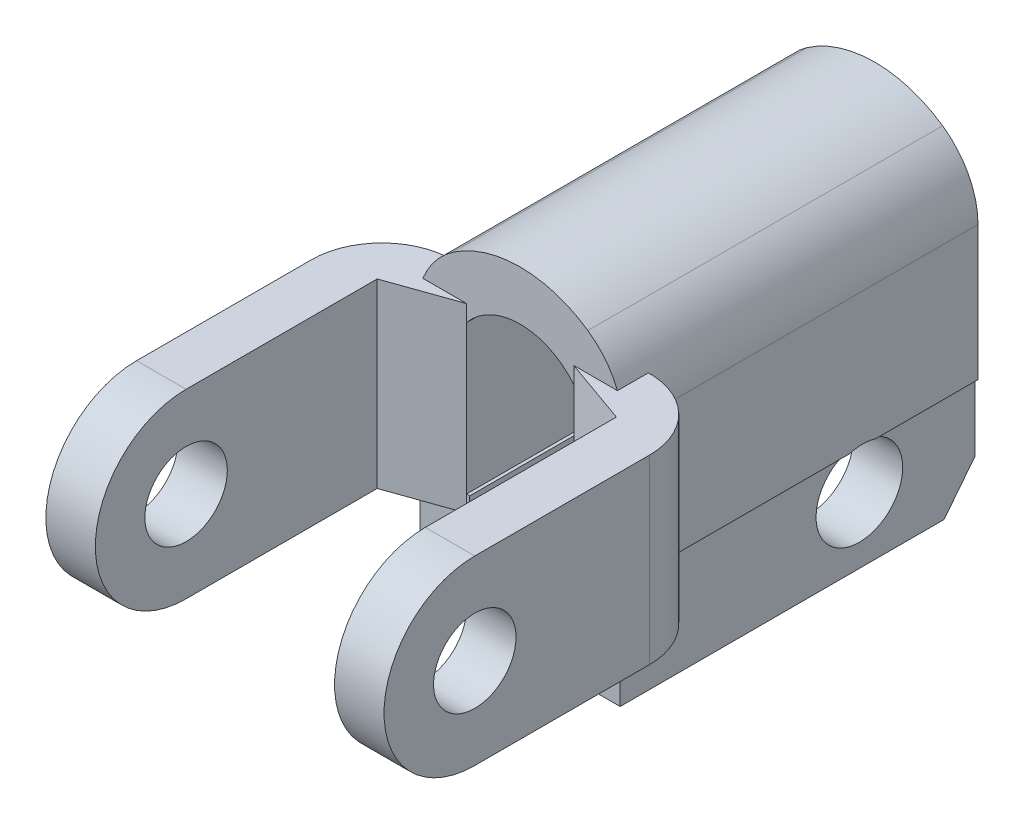
SolidWorks part; units mm, degrees
ref_plane "Front Plane" through (0, 0, 0) normal (0, 0, 1) x (1, 0, 0)
ref_plane "Top Plane" through (0, 0, 0) normal (0, 1, 0) x (1, 0, 0)
ref_plane "Right Plane" through (0, 0, 0) normal (1, 0, 0) x (0, 0, -1)
sketch "Sketch1" plane through (0, 0, 0) normal (0, 0, 1) x (1, 0, 0)
  line L0 (0, -9) -> (0, 9) construction
  line L1 (-6.5, 9) -> (-6.5, -9)
  line L2 (6.5, 9) -> (6.5, -9)
  line L3 (-6.5, -9) -> (-6.1191, -9)
  line L4 (-6.1191, -9) -> (-6.1191, -22)
  line L5 (6.1191, -9) -> (6.1191, -22)
  line L6 (6.5, -9) -> (6.1191, -9)
  line L7 (12.1191, -8.9892) -> (12.1191, -22)
  line L8 (12.5, -8.9892) -> (12.1191, -8.9892)
  line L9 (12.5, 7.3083) -> (12.5, -8.9892)
  line L10 (-12.5, 7.3083) -> (-12.5, -8.9607)
  line L11 (-12.5, -8.9607) -> (-12.1191, -8.9607)
  line L12 (-12.1191, -8.9607) -> (-12.1191, -22)
  line L13 (-12.1191, -22) -> (-6.1191, -22)
  line L14 (-6.1191, -22) -> (6.1191, -22) construction
  line L15 (6.1191, -22) -> (12.1191, -22)
  line L16 (-6.5, -9) -> (6.5, -9) construction
  arc A0 (-6.5, 9) -> (6.5, 9) centre (0, 3.7152) cw
  arc A1 (-8.2112, 15.517) -> (8.2112, 15.517) centre (0, 3.7152) cw
  arc A2 (12.5, 7.3083) -> (8.2112, 15.517) centre (2.5, 7.3083) ccw
  arc A3 (-8.2112, 15.517) -> (-12.5, 7.3083) centre (-2.5, 7.3083) ccw
  point P2 (0, 0)
  point P4 (-12.5, -15)
  point P5 (0, 0)
  dimension "D3" = 13
  dimension "D4" = 10
  dimension "D1" = 18
  dimension "D2" = 13
  dimension "D5" = 9
extrude "Boss-Extrude1" add sketch "Sketch1" along normal blind 43
sketch "Sketch2" plane through (0, 0, 0) normal (0, 1, 0) x (1, 0, 0)
  line L0 (0, 0) -> (0, -81) construction
  line L1 (-20.5, -81) -> (-20.5, -47.8201)
  line L2 (-20.5, -81) -> (-14.5, -81)
  line L3 (-14.5, -81) -> (-14.5, -45.8368)
  line L4 (-12.5, -43) -> (-12.5, 0) construction
  line L5 (-14.5, -81) -> (0, -81) construction
  line L6 (-14.5, -45.8368) -> (-6.5, -43)
  line L7 (-6.5, -43) -> (-6.5, -39.2728)
  line L8 (-6.5, -39.2728) -> (-12.5, -39.2728)
  line L9 (6.5, -39.2728) -> (12.5, -39.2728)
  line L10 (6.5, -43) -> (6.5, -39.2728)
  line L11 (14.5, -45.8368) -> (6.5, -43)
  line L12 (14.5, -81) -> (14.5, -45.8368)
  line L13 (20.5, -81) -> (14.5, -81)
  line L14 (20.5, -81) -> (20.5, -47.8201)
  arc A0 (-20.5, -47.8201) -> (-12.5, -39.2728) centre (-11.934, -47.8201) cw
  arc A1 (20.5, -47.8201) -> (12.5, -39.2728) centre (11.934, -47.8201) ccw
  point P13 (0, 0)
  point P14 (0, 0)
  dimension "D1" = 81
  dimension "D2" = 6
  dimension "D3" = 41
extrude "Boss-Extrude2" add sketch "Sketch2" along normal blind 11 and the other way blind 11
sketch "Sketch3" plane through (0, 0, 0) normal (1, 0, 0) x (0, 0, -1)
  line L0 (0, 0) -> (-81, 0) construction
  line L1 (-81, -11) -> (-81, 11) construction
  line L6 (0, -22) -> (0, -8.9892) construction
  line L8 (-43, -22) -> (0, -22) construction
  line L9 (-5.082, -23.7141) -> (2.0183, -14.6925)
  line L10 (2.0183, -14.6925) -> (6.529, -36.9123)
  line L11 (6.529, -36.9123) -> (-5.082, -23.7141)
  line L12 (-69, 11) -> (-69, 14.0189)
  line L13 (-69, 14.0189) -> (-85.2958, 14.0189)
  line L14 (-85.2958, 14.0189) -> (-85.2958, -20.3434)
  line L15 (-85.2958, -20.3434) -> (-69, -16.597)
  line L16 (-69, -16.597) -> (-69, -11)
  circle A0 centre (-14, -14) radius 5.25
  circle A1 centre (-69, 0) radius 5
  arc A2 (-69, 11) -> (-69, -11) centre (-69, 0) ccw
  dimension "D1" = 14
  dimension "D3" = 10.5
  dimension "D4" = 12
  dimension "D5" = 10
  dimension "D2" = 8
extrude "Cut-Extrude1" cut sketch "Sketch3" against normal through all both and the other way through all
sketch3d "3DSketch1"
  line L0 (20.5, 0, 69) -> (-20.5, 0, 69) construction
  line L1 (14.5, 0, 69) -> (20.5, 0, 69) construction
  line L2 (14.5, 0, 69) -> (20.5, 0, 69) construction
  line L3 (-20.5, 0, 69) -> (-14.5, 0, 69) construction
  line L4 (0, 0, 69) -> (0, 0, 0) construction
  circle A0 centre (-20.5, 0, 69) radius 5 construction
  point P8 (0, 0, 69)
  point P14 (-15.5, 0, 69)
